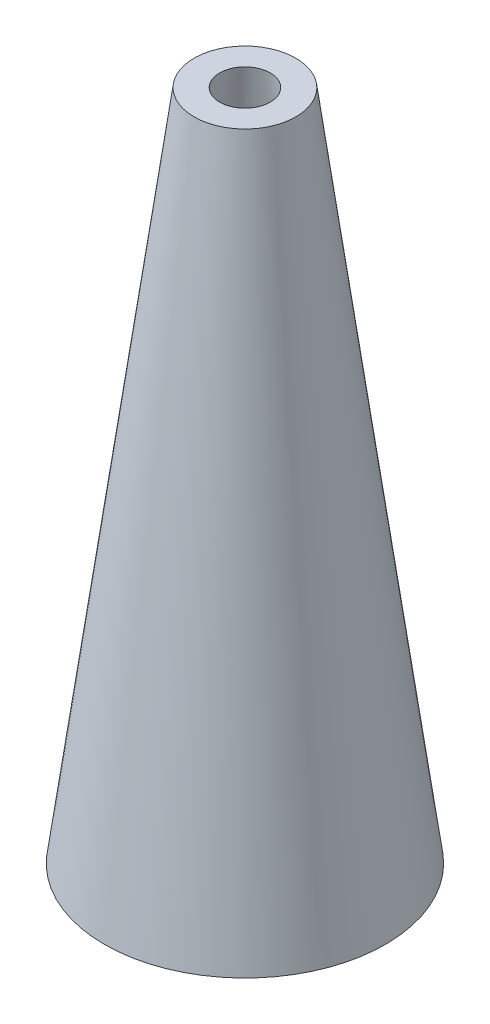
SolidWorks part; units mm, degrees
ref_plane "Front Plane" through (0, 0, 0) normal (0, 0, 1) x (1, 0, 0)
ref_plane "Top Plane" through (0, 0, 0) normal (0, 1, 0) x (1, 0, 0)
ref_plane "Right Plane" through (0, 0, 0) normal (1, 0, 0) x (0, 0, -1)
sketch "Sketch1" plane through (0, 0, 0) normal (0, 1, 0) x (1, 0, 0)
  circle A0 centre (0, 0) radius 5.5
  dimension "D2" = 11
extrude "Boss-Extrude1" add sketch "Sketch1" along normal blind 26.3 draft 7.6
sketch "Sketch2" plane through (0, 0, 0) normal (0, -1, 0) x (1, 0, 0)
  circle A0 centre (0, 0) radius 4.5
  dimension "D1" = 9
extrude "Cut-Extrude1" cut sketch "Sketch2" against normal blind 26.3 draft 7.6
